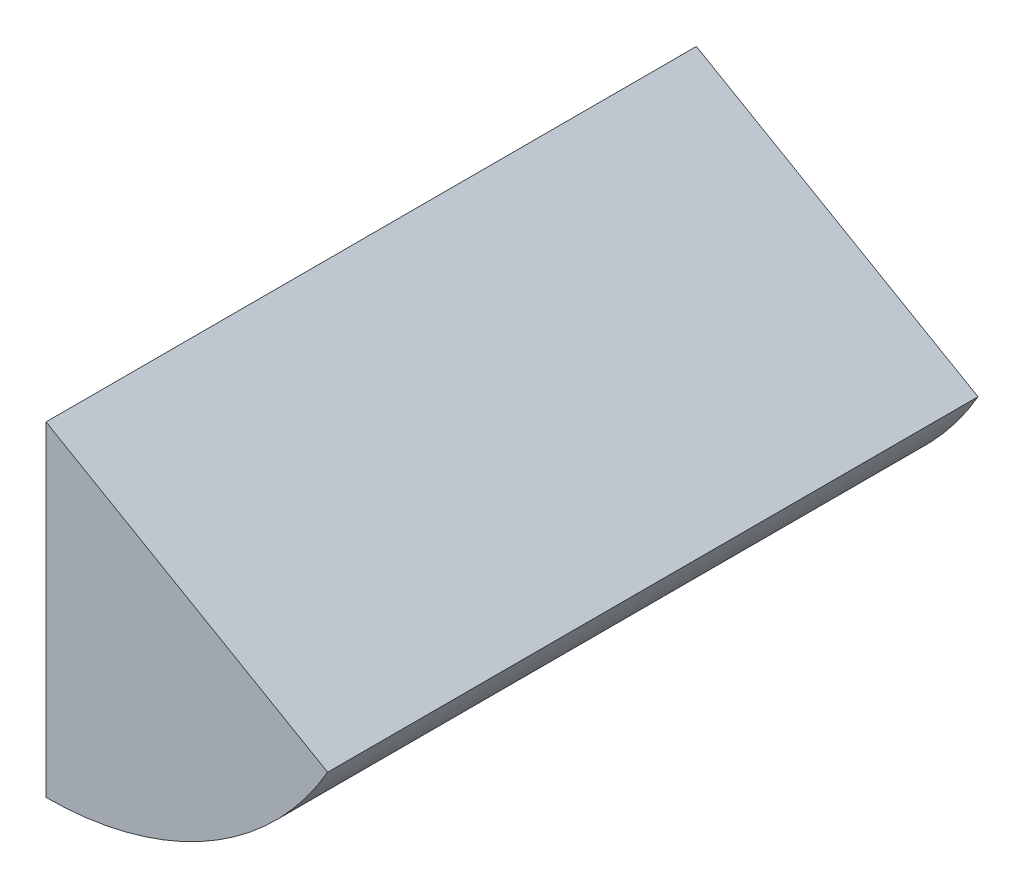
SolidWorks part; units mm, degrees
ref_plane "Alzado" through (0, 0, 0) normal (0, 0, 1) x (1, 0, 0)
ref_plane "Planta" through (0, 0, 0) normal (0, 1, 0) x (1, 0, 0)
ref_plane "Vista lateral" through (0, 0, 0) normal (1, 0, 0) x (0, 0, -1)
sketch "Croquis1" plane through (0, 0, 0) normal (0, 0, 1) x (1, 0, 0)
  line L0 (0, 0) -> (0, -25)
  line L1 (0, 0) -> (21.6506, -12.5)
  arc A0 (0, -25) -> (21.6506, -12.5) centre (0, 0) ccw
  dimension "D1" = 50
  dimension "D2" = 60
extrude "Saliente-Extruir1" add sketch "Croquis1" along normal blind 50
sketch "Croquis2" plane through (0, 0, 0) normal (0, 0, -1) x (-1, 0, 0)
  circle A0 centre (-7.9918, -13.8504) radius 5
  dimension "D1" = 10
extrude "Cortar-Extruir1" cut sketch "Croquis2" against normal blind 10
